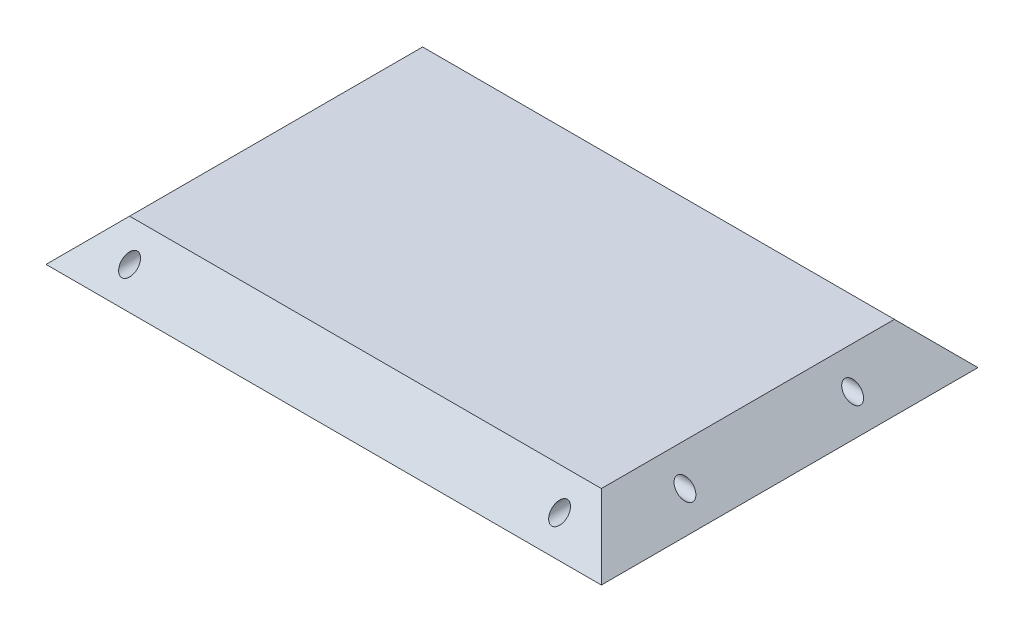
SolidWorks part; units mm, degrees
ref_plane "Спереди" through (0, 0, 0) normal (0, 0, 1) x (1, 0, 0)
ref_plane "Сверху" through (0, 0, 0) normal (0, 1, 0) x (1, 0, 0)
ref_plane "Справа" through (0, 0, 0) normal (1, 0, 0) x (0, 0, -1)
sketch "Эскиз1" plane through (0, 0, 0) normal (0, 1, 0) x (1, 0, 0)
  line L1 (-66.449, -45.0616) -> (66.449, -45.0616)
  line L2 (-66.449, -45.0616) -> (-66.449, 45.0616)
  line L3 (-66.449, 45.0616) -> (66.449, 45.0616)
  line L4 (66.449, -45.0616) -> (66.449, 45.0616)
  line L5 (-66.449, -45.0616) -> (66.449, 45.0616) construction
  line L6 (-66.449, 45.0616) -> (66.449, -45.0616) construction
  point P0 (0, 0)
ref_plane "Плоскость1" through (0, 10, 0) normal (0, 1, 0) x (1, 0, 0)
sketch "Эскиз2" plane through (0, 10, 0) normal (0, 1, 0) x (1, 0, 0)
  line L4 (-66.449, -45.0616) -> (66.449, -45.0616) construction
  line L5 (66.449, -45.0616) -> (66.449, 45.0616) construction
  line L6 (-66.449, 45.0616) -> (66.449, 45.0616) construction
  line L7 (-66.449, -45.0616) -> (-66.449, 45.0616) construction
  line L8 (56.449, 35.0616) -> (-56.449, 35.0616)
  line L9 (56.449, -35.0616) -> (56.449, 35.0616)
  line L10 (-56.449, 35.0616) -> (-56.449, -35.0616)
  line L11 (-56.449, -35.0616) -> (56.449, -35.0616)
  line L12 (56.449, 35.0616) -> (-56.449, 35.0616)
  line L13 (56.449, -35.0616) -> (56.449, 35.0616)
  line L14 (-56.449, 35.0616) -> (-56.449, -35.0616)
  line L15 (-56.449, -35.0616) -> (56.449, -35.0616)
  line L16 (-66.449, -45.0616) -> (66.449, -45.0616) construction
  line L17 (66.449, -45.0616) -> (66.449, 45.0616) construction
  line L18 (-66.449, 45.0616) -> (66.449, 45.0616) construction
  line L19 (-66.449, -45.0616) -> (-66.449, 45.0616) construction
  line L20 (-56.449, -35.0616) -> (-56.449, -45.0616) construction
  line L21 (-56.449, -35.0616) -> (-66.449, -35.0616) construction
  line L22 (-56.449, 35.0616) -> (-56.449, 45.0616) construction
  line L23 (-56.449, 35.0616) -> (-66.449, 35.0616) construction
  line L24 (56.449, -35.0616) -> (56.449, -45.0616) construction
  line L25 (56.449, -35.0616) -> (66.449, -35.0616) construction
  line L26 (56.449, 35.0616) -> (56.449, 45.0616) construction
  line L27 (56.449, 35.0616) -> (66.449, 35.0616) construction
  dimension "D1" = 10
loft "По сечениям1" add profiles "Эскиз1", "Эскиз2"
ref_plane "Плоскость2" through (0, 0, 45.0616) normal (0, 0, 1) x (1, 0, 0)
sketch "Эскиз3" plane through (0, 0, 45.0616) normal (0, 0, 1) x (1, 0, 0)
  line L0 (-66.449, 0) -> (-66.449, 10) construction
  line L1 (66.449, 0) -> (66.449, 10) construction
  line L2 (-66.449, 10) -> (66.449, 10) construction
  line L3 (56.449, 0) -> (56.449, 10) construction
  line L4 (-66.449, 0) -> (66.449, 0) construction
  line L5 (46.449, 10) -> (46.449, 5) construction
  line L6 (46.449, 5) -> (51.449, 5) construction
  line L7 (51.449, 5) -> (56.449, 5) construction
  line L8 (-66.449, 10) -> (66.449, 10) construction
  line L9 (0, 10) -> (0, 0) construction
  circle A0 centre (51.449, 5) radius 1.85
  circle A1 centre (-51.449, 5) radius 1.85
  dimension "D1" = 3.7
  dimension "D2" = 10
ref_plane "Плоскость3" through (0, 0, -45.0616) normal (0, 0, -1) x (-1, 0, 0)
extrude "Вырез-Вытянуть1" cut sketch "Эскиз3" against normal blind 20 contours A0 | A1
mirror "Зеркальное отражение1" about plane through (0, 0, 0) normal (0, 0, 1) of "Вырез-Вытянуть1"
ref_plane "Плоскость4" through (66.449, 0, 0) normal (1, 0, 0) x (0, 0, -1)
sketch "Эскиз4" plane through (66.449, 0, 0) normal (1, 0, 0) x (0, 0, -1)
  line L0 (-45.0616, 10) -> (-45.0616, 0) construction
  line L1 (-45.0616, 10) -> (45.0616, 10) construction
  line L2 (45.0616, 10) -> (45.0616, 0) construction
  line L3 (-45.0616, 10) -> (45.0616, 10) construction
  line L4 (-25.0616, 0) -> (-25.0616, 10) construction
  line L5 (-45.0616, 0) -> (45.0616, 0) construction
  line L6 (-15.0616, 10) -> (-15.0616, 0) construction
  line L7 (-25.0616, 5) -> (-15.0616, 5) construction
  line L8 (0, 10) -> (0, 0) construction
  circle A0 centre (-20.0616, 5) radius 1.85
  circle A1 centre (20.0616, 5) radius 1.85
  dimension "D3" = 3.7
  dimension "D1" = 20
  dimension "D2" = 10
extrude "Вырез-Вытянуть2" cut sketch "Эскиз4" against normal blind 20 contours A1 | A0
mirror "Зеркальное отражение2" about plane through (0, 0, 0) normal (1, 0, 0) of "Вырез-Вытянуть2"
